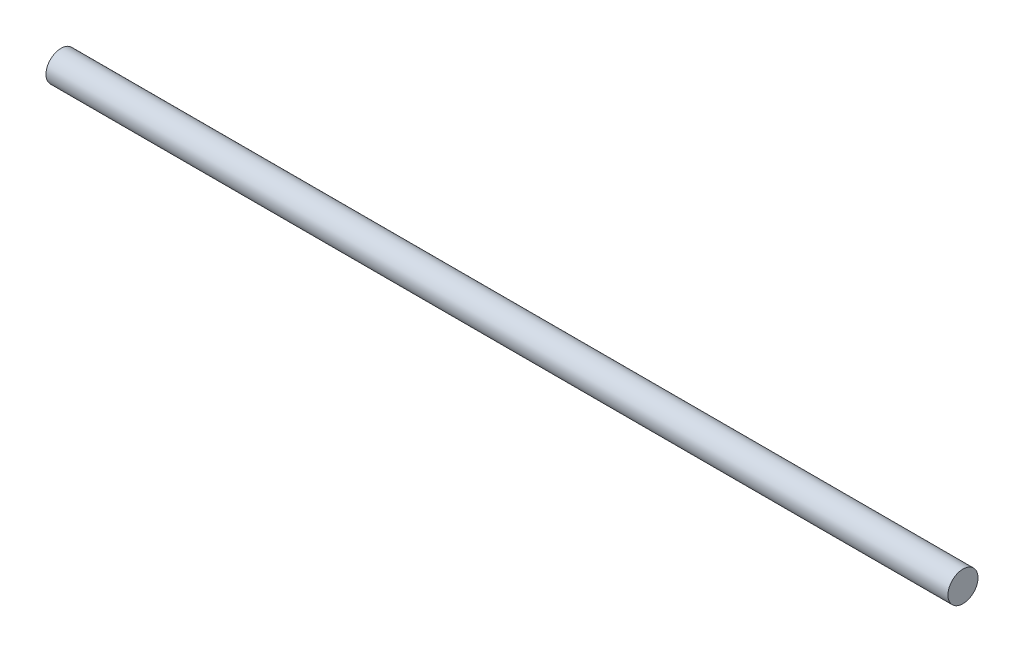
SolidWorks part; units mm, degrees
ref_plane "Front Plane" through (0, 0, 0) normal (0, 0, 1) x (1, 0, 0)
ref_plane "Top Plane" through (0, 0, 0) normal (0, 1, 0) x (1, 0, 0)
ref_plane "Right Plane" through (0, 0, 0) normal (1, 0, 0) x (0, 0, -1)
sketch "Sketch1" plane through (0, 0, 0) normal (1, 0, 0) x (0, 0, -1)
  circle A0 centre (0, 0) radius 2
extrude "Boss-Extrude1" add sketch "Sketch1" along normal blind 120
